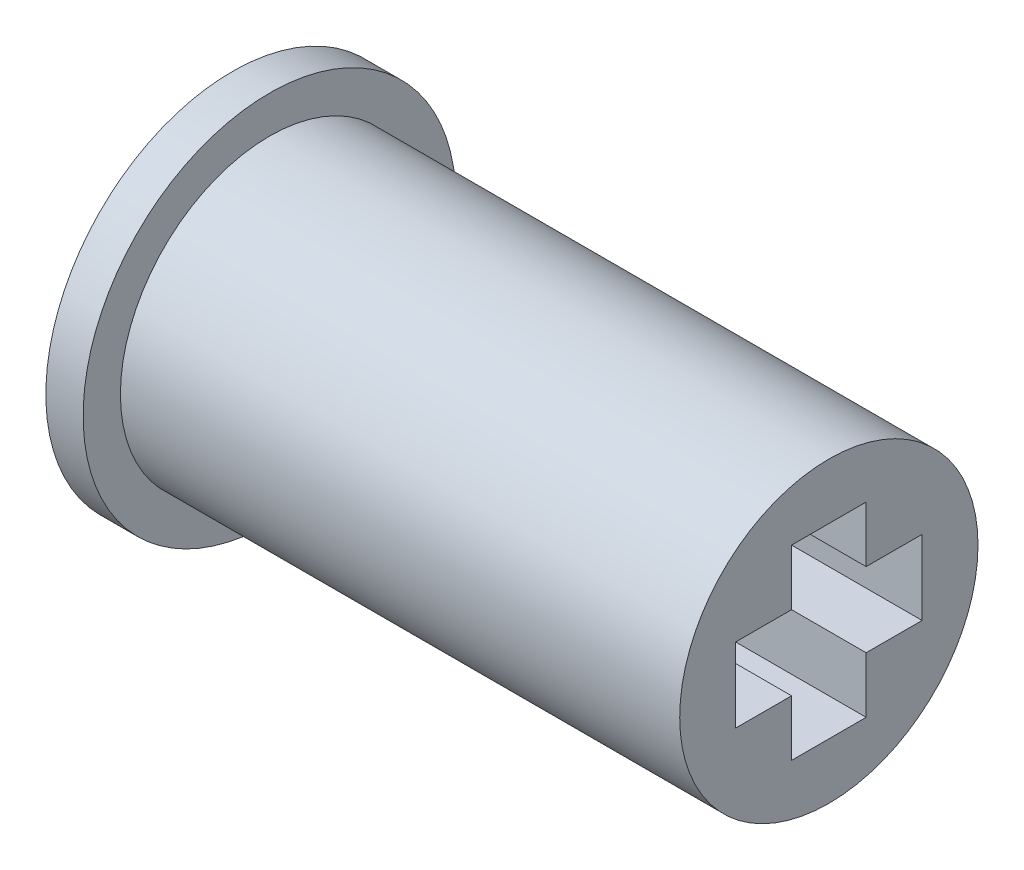
SolidWorks part; units mm, degrees
ref_plane "Front Plane" through (0, 0, 0) normal (0, 0, 1) x (1, 0, 0)
ref_plane "Top Plane" through (0, 0, 0) normal (0, 1, 0) x (1, 0, 0)
ref_plane "Right Plane" through (0, 0, 0) normal (1, 0, 0) x (0, 0, -1)
sketch "Sketch1" plane through (0, 0, 0) normal (1, 0, 0) x (0, 0, -1)
  circle A0 centre (0, 0) radius 5
  dimension "D1" = 10
extrude "Boss-Extrude2" add sketch "Sketch1" along normal blind 1 contours A0
sketch "Sketch2" plane through (1, 0, 0) normal (1, 0, 0) x (0, 0, -1)
  circle A0 centre (0, 0) radius 4
  dimension "D1" = 8
extrude "Boss-Extrude3" add sketch "Sketch2" along normal blind 15
sketch "Sketch4" plane through (16, 0, 0) normal (1, 0, 0) x (0, 0, -1)
  line L0 (0, 2.5) -> (-1, 2.5)
  line L1 (-1, 0) -> (-1, 2.5)
  line L2 (0, 2.5) -> (1, 2.5)
  line L3 (1, 0) -> (1, 2.5)
  line L4 (-0.6041, -2.5) -> (-1, -2.5)
  line L5 (-1, 0) -> (-1, -2.5)
  line L6 (-0.6041, -2.5) -> (1, -2.5)
  line L7 (1, 0) -> (1, -2.5)
  line L8 (0, 1) -> (2.5, 1)
  line L9 (2.5, 0) -> (2.5, 1)
  line L10 (-0.6041, -1) -> (2.5, -1)
  line L11 (2.5, 0) -> (2.5, -1)
  line L12 (0, 1) -> (-2.5, 1)
  line L13 (-2.5, 0) -> (-2.5, 1)
  line L14 (-0.6041, -1) -> (-2.5, -1)
  line L15 (-2.5, 0) -> (-2.5, -1)
  circle A0 centre (0, 0) radius 4 construction
  circle A1 centre (0, 0) radius 4
  dimension "D1" = 1.5
  dimension "D2" = 1.5
  dimension "D3" = 1.5
  dimension "D4" = 1.5
  dimension "D5" = 2.5
  dimension "D6" = 2.5
  dimension "D7" = 2.5
  dimension "D8" = 1
  dimension "D9" = 1
  dimension "D10" = 2.5
  dimension "D11" = 2
  dimension "D12" = 2
  dimension "D13" = 2.5
  dimension "D14" = 2.5
extrude "Cut-Extrude1" cut sketch "Sketch4" against normal blind 15 contours L12 L8 L3 L2 L0 L1 | L14 L10 L7 L3 L8 L12 L1 L5 | L11 L9 L8 L3 L7 L10 | L13 L15 L14 L5 L1 L12 | L10 L14 L5 L4 L6 L7
